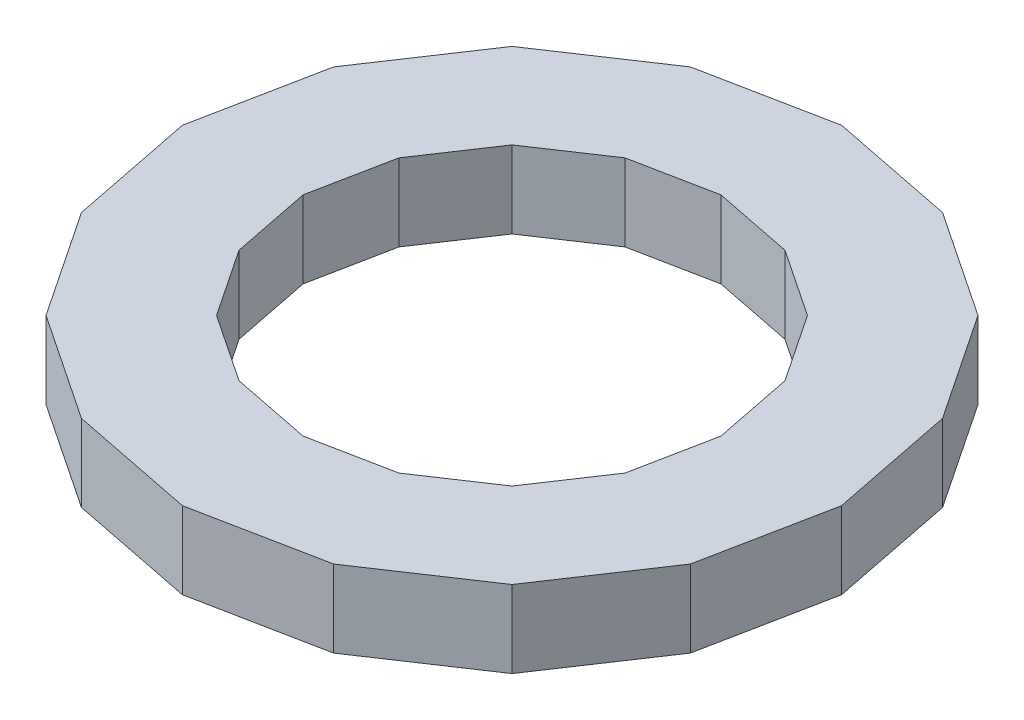
SolidWorks part; units mm, degrees
ref_plane "Front Plane" through (0, 0, 0) normal (0, 0, 1) x (1, 0, 0)
ref_plane "Top Plane" through (0, 0, 0) normal (0, 1, 0) x (1, 0, 0)
ref_plane "Right Plane" through (0, 0, 0) normal (1, 0, 0) x (0, 0, -1)
sketch "Sketch2" plane through (0, 0, 0) normal (0, 1, 0) x (1, 0, 0)
  line L0 (0, 0) -> (-51.5903, 0) construction
  line L1 (-81.3726, 0) -> (-75.1784, -31.1399)
  line L2 (-75.1784, -31.1399) -> (-57.5391, -57.5391)
  line L3 (-57.5391, -57.5391) -> (-31.1399, -75.1784)
  line L4 (-31.1399, -75.1784) -> (0, -81.3726)
  line L5 (0, -81.3726) -> (31.1399, -75.1784)
  line L6 (31.1399, -75.1784) -> (57.5391, -57.5391)
  line L7 (57.5391, -57.5391) -> (75.1784, -31.1399)
  line L8 (75.1784, -31.1399) -> (81.3726, 0)
  line L9 (81.3726, 0) -> (75.1784, 31.1399)
  line L10 (75.1784, 31.1399) -> (57.5391, 57.5391)
  line L11 (57.5391, 57.5391) -> (31.1399, 75.1784)
  line L12 (31.1399, 75.1784) -> (0, 81.3726)
  line L13 (0, 81.3726) -> (-31.1399, 75.1784)
  line L14 (-31.1399, 75.1784) -> (-57.5391, 57.5391)
  line L15 (-57.5391, 57.5391) -> (-75.1784, 31.1399)
  line L16 (-75.1784, 31.1399) -> (-81.3726, 0)
  line L17 (-51.5903, 0) -> (-47.6632, -19.7428)
  line L18 (-47.6632, -19.7428) -> (-36.4799, -36.4799)
  line L19 (-36.4799, -36.4799) -> (-19.7428, -47.6632)
  line L20 (-19.7428, -47.6632) -> (0, -51.5903)
  line L21 (0, -51.5903) -> (19.7428, -47.6632)
  line L22 (19.7428, -47.6632) -> (36.4799, -36.4799)
  line L23 (36.4799, -36.4799) -> (47.6632, -19.7428)
  line L24 (47.6632, -19.7428) -> (51.5903, 0)
  line L25 (51.5903, 0) -> (47.6632, 19.7428)
  line L26 (47.6632, 19.7428) -> (36.4799, 36.4799)
  line L27 (36.4799, 36.4799) -> (19.7428, 47.6632)
  line L28 (19.7428, 47.6632) -> (0, 51.5903)
  line L29 (0, 51.5903) -> (-19.7428, 47.6632)
  line L30 (-19.7428, 47.6632) -> (-36.4799, 36.4799)
  line L31 (-36.4799, 36.4799) -> (-47.6632, 19.7428)
  line L32 (-47.6632, 19.7428) -> (-51.5903, 0)
  line L33 (-81.3726, 0) -> (-51.5903, 0) construction
  line L34 (-51.5903, 0) -> (-51.8143, 0.8915) construction
  circle A0 centre (0, 0) radius 79.809 construction
  circle A1 centre (0, 0) radius 50.599 construction
  dimension "D1" = 31.75
  dimension "D2" = 29.21
extrude "Boss-Extrude2" add sketch "Sketch2" along normal blind 19.05
